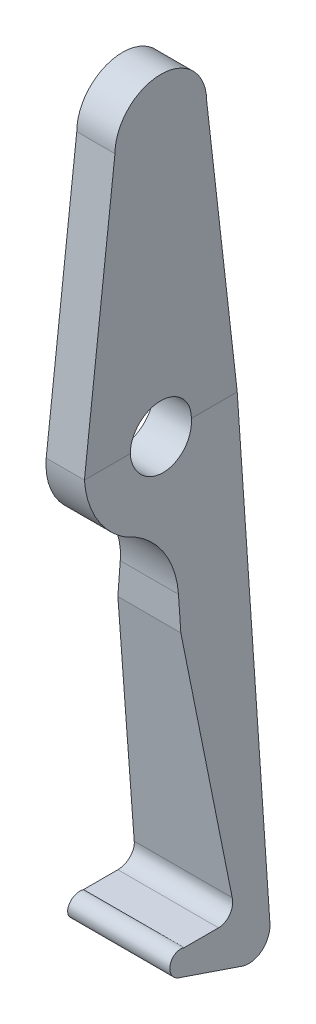
SolidWorks part; units mm, degrees
ref_plane "Front Plane" through (0, 0, 0) normal (0, 0, 1) x (1, 0, 0)
ref_plane "Top Plane" through (0, 0, 0) normal (0, 1, 0) x (1, 0, 0)
ref_plane "Right Plane" through (0, 0, 0) normal (1, 0, 0) x (0, 0, -1)
sketch "Sketch2" plane through (0, 0, 0) normal (1, 0, 0) x (0, 0, -1)
  line L0 (0, 0) -> (0, -35) construction
  line L1 (-6, 0) -> (-10, -35)
  line L2 (-10, -35) -> (10, -35)
  line L3 (10, -35) -> (6, 0)
  line L5 (10, -35) -> (10, -57)
  line L7 (1, -57) -> (1, -52.7824)
  line L8 (-5.2445, -43.5144) -> (10, -35)
  line L9 (10, -57) -> (10, -93.063)
  line L10 (6.3884, -96) -> (-1.9635, -93.2863)
  line L11 (-1.0365, -90.4331) -> (3.4635, -90.4331)
  line L12 (5.4331, -88.0856) -> (1, -57)
  line L13 (6.3884, -96) -> (-10, -96) construction
  arc A0 (6, 0) -> (-6, 0) centre (0, 0) ccw
  circle A1 centre (0, -35) radius 10
  circle A2 centre (0, -35) radius 4
  arc A3 (1, -52.7824) -> (-5.2445, -43.5144) centre (-9, -52.7824) ccw
  arc A4 (10, -93.063) -> (6.3884, -96) centre (7, -93.063) cw
  arc A5 (-1.9635, -93.2863) -> (-1.0365, -90.4331) centre (-1.5, -91.8597) cw
  arc A6 (3.4635, -90.4331) -> (5.4331, -88.0856) centre (3.4635, -88.4331) ccw
  dimension "D1" = 12
  dimension "D2" = 20
  dimension "D4" = 8
  dimension "D5" = 10
  dimension "D9" = 2
  dimension "D10" = 4.5
  dimension "D8" = 3
  dimension "D11" = 1.5
  dimension "D3" = 35
  dimension "D6" = 9
  dimension "D7" = 22
  dimension "D12" = 18
  dimension "D13" = 8.5
  dimension "D14" = 96
extrude "Boss-Extrude1" add sketch "Sketch2" along normal blind 14 contours A1 L3 A0 L1 | A2 L2 L3 A1 L1 | A2 L2 A1 L8 | A6 L11 A5 L10 A4 L9 L5 A1 A3 L7 L12 | A3 A1 L8
sketch "Sketch5" plane through (0, 0, -10) normal (0, 0, -1) x (-1, 0, 0)
  line L0 (0, -96.063) -> (-14, -96.063)
  line L1 (-14, -96.063) -> (-9.5, -35)
  line L2 (-14, -35) -> (0, -35) construction
  line L3 (-9.5, -35) -> (-9.5, 6)
  line L4 (0, 6) -> (-14, 6) construction
  line L5 (-9.5, 6) -> (-4.5, 6)
  line L6 (-4.5, 6) -> (-4.5, -35)
  line L7 (-4.5, -35) -> (0, -96.063)
  line L8 (-14, 6) -> (0, 6) construction
  point P7 (-7, 6)
  dimension "D1" = 5
extrude "Cut-Extrude1" cut sketch "Sketch5" against normal through all flip side to cut
